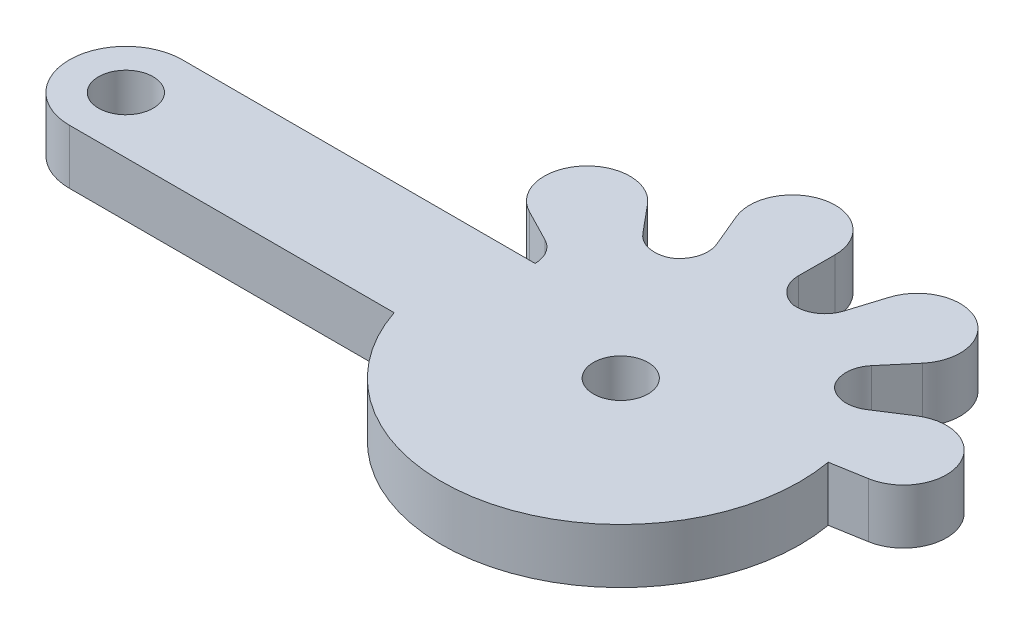
SolidWorks part; units mm, degrees
ref_plane "Alzado" through (0, 0, 0) normal (0, 0, 1) x (1, 0, 0)
ref_plane "Planta" through (0, 0, 0) normal (0, 1, 0) x (1, 0, 0)
ref_plane "Vista lateral" through (0, 0, 0) normal (1, 0, 0) x (0, 0, -1)
sketch "Croquis1" plane through (0, 0, 0) normal (0, 1, 0) x (1, 0, 0)
  line L0 (0, 0) -> (-27.1616, 0) construction
  line L1 (-27.1616, -3.105) -> (-9.332, -3.105)
  line L2 (-27.1616, 3.105) -> (-7.8094, 3.105)
  line L3 (0, 0) -> (-9.3507, 7.5049) construction
  line L4 (-9.3507, 7.5049) -> (-9.3794, 3.105) construction
  line L5 (-5.0613, 8.4851) -> (-9.3507, 7.5049) construction
  line L6 (0, 0) -> (-5.0613, 8.4851) construction
  line L7 (0, 0) -> (-9.3794, 3.105) construction
  line L8 (-8.6599, 4.5004) -> (-10.4295, 5.4129)
  line L9 (-7.5418, 9.0108) -> (-6.2679, 7.4806)
  line L10 (0.0147, 11.7505) -> (0.0069, 9.7595)
  line L11 (-3.741, 9.014) -> (-4.5101, 10.8505)
  line L12 (7.5643, 8.9919) -> (6.2786, 7.4717)
  line L13 (2.9283, 9.3098) -> (3.5196, 11.211)
  line L14 (11.5745, 2.026) -> (9.6868, 1.7007)
  line L15 (8.2274, 5.2495) -> (9.9025, 6.3257)
  line L16 (0, 0) -> (-4.257, 7.1368) construction
  line L17 (0, 0) -> (1.3264, 8.2035) construction
  circle A1 centre (0, 0) radius 1.5
  circle A2 centre (-27.1616, 0) radius 1.5
  arc A3 (-27.1616, 3.105) -> (-27.1616, -3.105) centre (-27.1616, 0) ccw
  arc A4 (-7.5418, 9.0108) -> (-10.4295, 5.4129) centre (-9.3507, 7.5049) ccw
  arc A5 (-6.2679, 7.4806) -> (-4.3117, 7.1056) centre (-5.0613, 8.4851) ccw
  arc A6 (-7.8094, 3.105) -> (-8.6599, 4.5004) centre (-9.3794, 3.105) ccw
  circle A7 centre (0, 0) radius 8.31 construction
  arc A8 (0.0147, 11.7505) -> (-4.5101, 10.8505) centre (-2.339, 11.7596) ccw
  arc A9 (0.0069, 9.7595) -> (1.2644, 8.2148) centre (1.5769, 9.7533) ccw
  arc A10 (-4.3117, 7.1056) -> (-3.741, 9.014) centre (-5.1892, 8.4075) ccw
  arc A11 (7.5643, 8.9919) -> (3.5196, 11.211) centre (5.7671, 10.5119) ccw
  arc A12 (6.2786, 7.4717) -> (6.249, 5.4801) centre (7.4773, 6.4579) ccw
  arc A13 (1.2644, 8.2148) -> (2.9283, 9.3098) centre (1.4291, 9.7761) ccw
  arc A14 (11.5745, 2.026) -> (9.9025, 6.3257) centre (11.1748, 4.3455) ccw
  arc A15 (-9.332, -3.105) -> (9.6868, 1.7007) centre (0, 0) ccw
  arc A16 (6.249, 5.4801) -> (8.2274, 5.2495) centre (7.3787, 6.5703) ccw
  arc A23 (9.6872, 1.6989) -> (9.6124, 1.6879) centre (9.879, 0.1407) ccw [skipped]
  point P16 (1.2644, 8.2148)
  point P32 (6.249, 5.4801)
  point P39 (-4.3117, 7.1056)
  dimension "D2" = 4.7075
  dimension "D5" = 4.4
  dimension "D8" = 3.14
  dimension "D9" = 3.14
  dimension "D10" = 3
  dimension "D11" = 6.21
  dimension "D12" = 3
  dimension "D3" = 11.99
  dimension "D4" = 4.4
  dimension "D6" = 9.88
  dimension "D7" = 9.88
  dimension "D14" = 40
  dimension "D13" = 4
extrude "Saliente-Extruir1" add sketch "Croquis1" along normal blind 3
